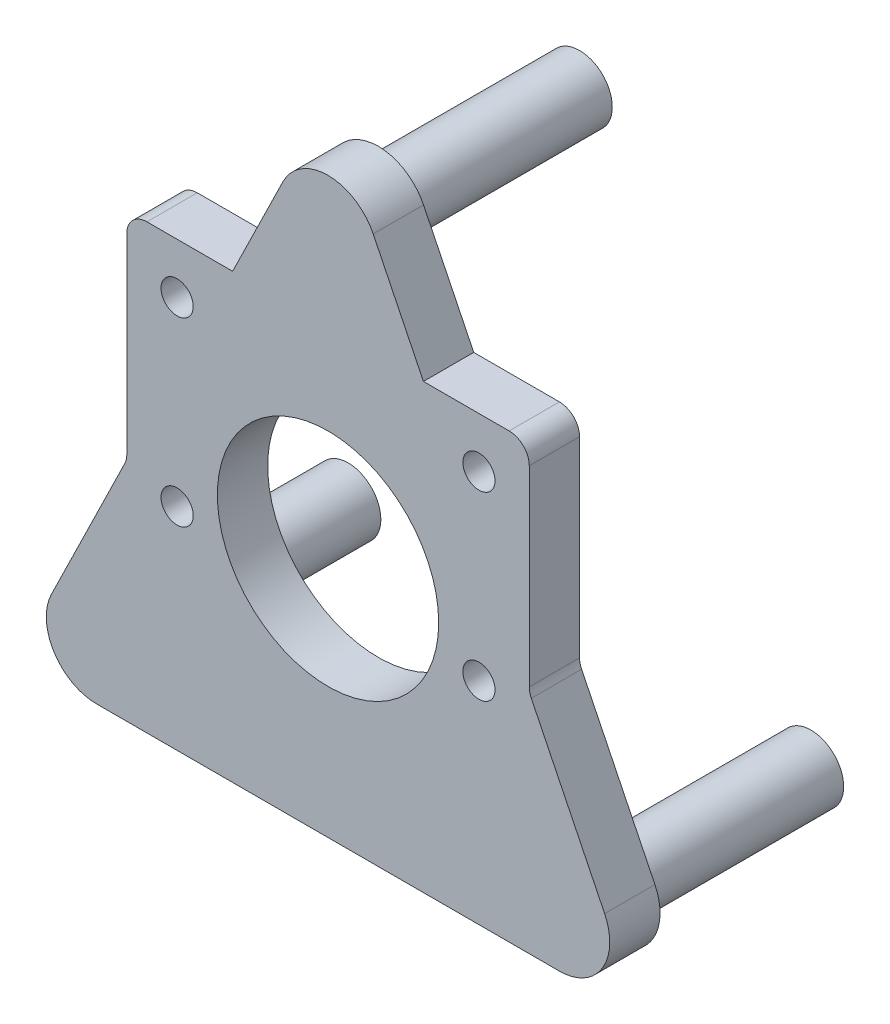
SolidWorks part; units mm, degrees
ref_plane "前视基准面" through (0, 0, 0) normal (0, 0, 1) x (1, 0, 0)
ref_plane "上视基准面" through (0, 0, 0) normal (0, 1, 0) x (1, 0, 0)
ref_plane "右视基准面" through (0, 0, 0) normal (1, 0, 0) x (0, 0, -1)
other "Configuration Table"
sketch "草图1" plane through (0, 0, 0) normal (0, 0, 1) x (1, 0, 0)
  line L0 (-4.4911, 30.1978) -> (-27.4911, -16.8022)
  line L1 (-23, -24) -> (23, -24)
  line L2 (0, -55) -> (0, 55) construction
  line L3 (4.4911, 30.1978) -> (27.4911, -16.8022)
  circle A0 centre (0, 0) radius 28 construction
  arc A1 (4.4911, 30.1978) -> (-4.4911, 30.1978) centre (0, 28) ccw
  circle A2 centre (26.6296, 8.6525) radius 6 construction
  arc A3 (23, -24) -> (27.4911, -16.8022) centre (23, -19) ccw
  arc A4 (-27.4911, -16.8022) -> (-23, -24) centre (-23, -19) ccw
  circle A5 centre (-26.6296, 8.6525) radius 6 construction
  circle A6 centre (0, 0) radius 11
  point P15 (0, 0)
  point P16 (0, 0)
  dimension "D1" = 56
  dimension "D2" = 10
  dimension "D4" = 22
  dimension "D3" = 5
  dimension "D5" = 5
  dimension "D6" = 23
  dimension "D7" = 19
  dimension "D8" = 19
extrude "凸台-拉伸1" add sketch "草图1" along normal blind 5
sketch "草图2" plane through (0, 0, 0) normal (0, 0, -1) x (-1, 0, 0)
  circle A0 centre (0, 28) radius 3.25
  circle A1 centre (-23, -19) radius 3.25
  circle A2 centre (23, -19) radius 3.25
  dimension "D1" = 6.5
  dimension "D2" = 6.5
  dimension "D3" = 6.5
extrude "凸台-拉伸2" add sketch "草图2" along normal blind 20
fillet "圆角1" radius 1 3 edges at (-19.75, -19, 0) (26.25, -19, 0) (3.25, 28, 0)
sketch "草图3" plane through (0, 0, 5) normal (0, 0, 1) x (1, 0, 0)
  line L0 (0, -55) -> (0, 55) construction
  line L1 (-20, 20) -> (-9.4815, 20)
  line L2 (-20, 20) -> (-20, -1.4944)
  line L4 (20, 20) -> (20, -1.4944)
  line L5 (-4.4911, 30.1978) -> (-27.4911, -16.8022) construction
  line L6 (-9.4815, 20) -> (-20, -1.4944)
  line L7 (27.4911, -16.8022) -> (4.4911, 30.1978) construction
  line L8 (20, -1.4944) -> (9.4815, 20)
  line L9 (9.4815, 20) -> (20, 20)
  circle A0 centre (-15, 15) radius 1.6 construction
  circle A1 centre (0, 0) radius 11 construction
  circle A2 centre (15, 15) radius 1.6 construction
  dimension "D1" = 3.2
  dimension "D2" = 15
  dimension "D3" = 15
  dimension "D4" = 5
  dimension "D5" = 5
  dimension "D7" = 5
extrude "凸台-拉伸3" add sketch "草图3" against normal blind 5
fillet "圆角2" radius 2 4 edges at (20, -1.4944, 2.5) (-20, -1.4944, 2.5) (20, 20, 2.5) (-20, 20, 2.5)
sketch "草图4" plane through (0, 0, 5) normal (0, 0, 1) x (1, 0, 0)
  line L0 (-15, 15) -> (15, 15) construction
  line L1 (-15, 15) -> (-15, -3) construction
  circle A0 centre (-15, 15) radius 1.6
  circle A1 centre (15, 15) radius 1.6
  circle A2 centre (15, -3) radius 1.6
  circle A3 centre (-15, -3) radius 1.6
  dimension "D1" = 3.2
  dimension "D2" = 15
  dimension "D3" = 15
  dimension "D6" = 90
  dimension "D7" = 30
  dimension "D4" = 2
  dimension "D5" = 2
extrude "切除-拉伸1" cut sketch "草图4" against normal blind 5
